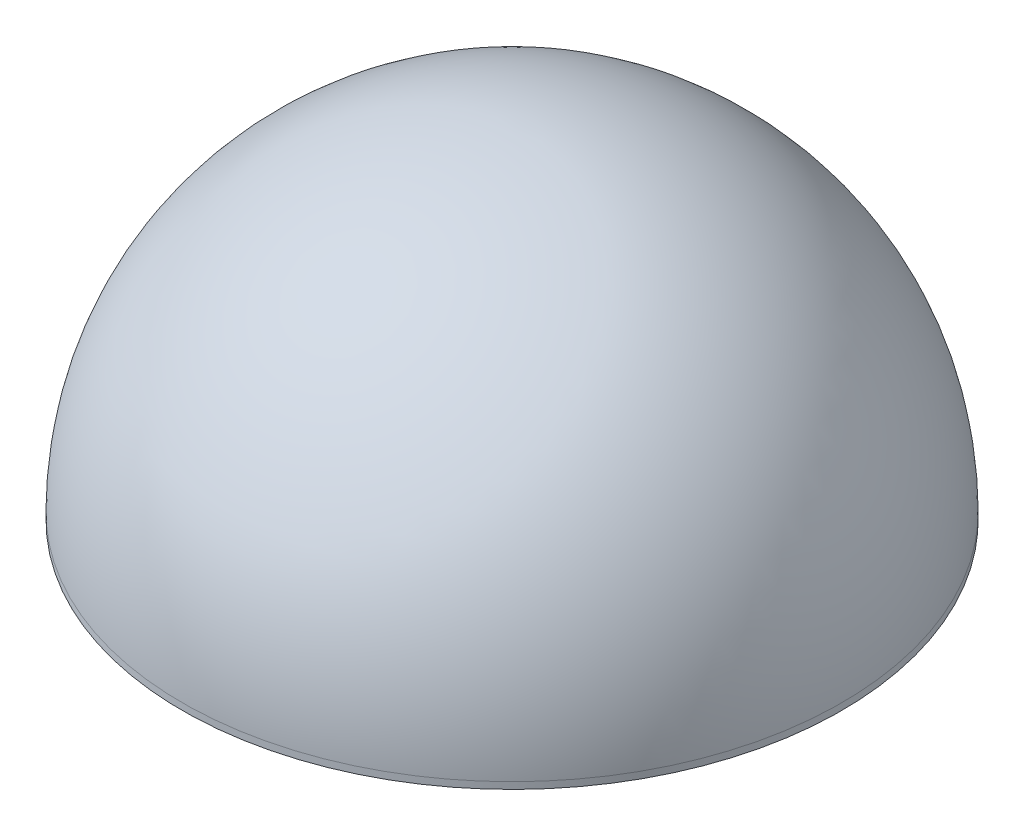
SolidWorks part; units mm, degrees
ref_plane "Front Plane" through (0, 0, 0) normal (0, 0, 1) x (1, 0, 0)
ref_plane "Top Plane" through (0, 0, 0) normal (0, 1, 0) x (1, 0, 0)
ref_plane "Right Plane" through (0, 0, 0) normal (1, 0, 0) x (0, 0, -1)
sketch "Sketch1" plane through (0, 0, 0) normal (0, 0, 1) x (1, 0, 0)
  line L0 (0, 0) -> (0, 67.3314) construction
  line L1 (0, 0) -> (-6.223, 0)
  line L2 (55, 0) -> (-55, 0) construction
  line L3 (0, 6.35) -> (1.7197, 6.35) construction
  line L7 (-6.223, 0) -> (-6.223, 0.127)
  line L8 (0, 6.35) -> (0, 0)
  arc A0 (-6.223, 0.127) -> (0, 6.35) centre (0, 0.127) cw
  dimension "D1" = 6.35
  dimension "D2" = 6.223
revolve "Revolve1" add sketch "Sketch1" angle 360 about L0
sketch "Sketch2" plane through (0, 0, 0) normal (0, -1, 0) x (1, 0, 0)
  circle A0 centre (0, 0) radius 1.5
  dimension "D1" = 3
extrude "Cut-Extrude1" cut sketch "Sketch2" against normal blind 3.175
